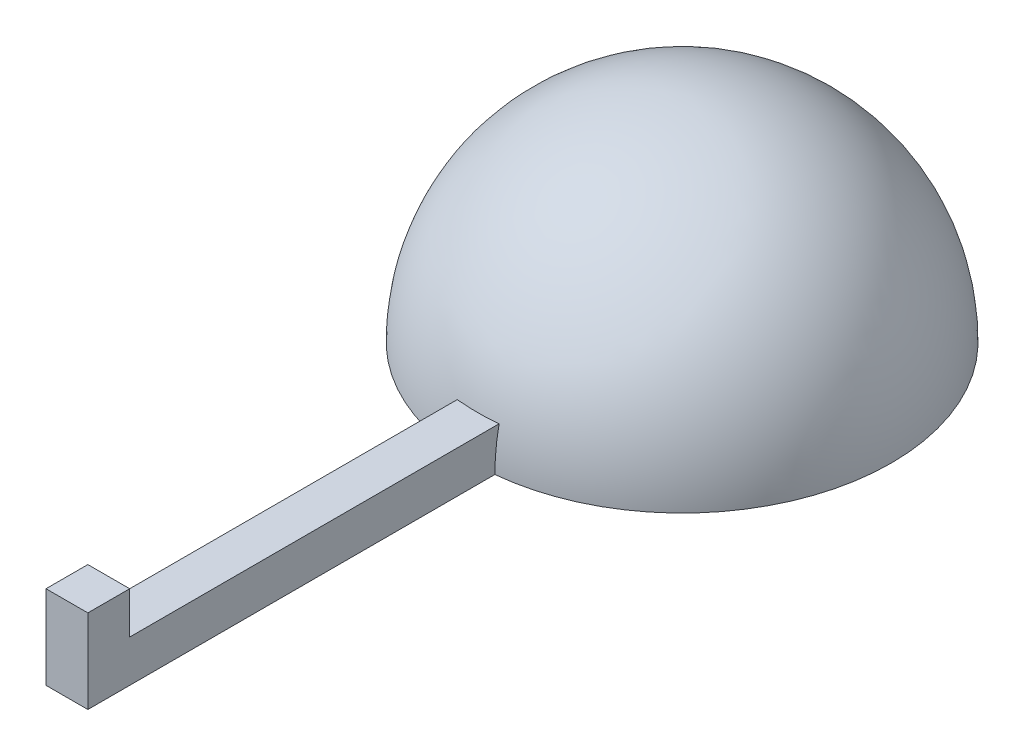
SolidWorks part; units mm, degrees
ref_plane "Front Plane" through (0, 0, 0) normal (0, 0, 1) x (1, 0, 0)
ref_plane "Top Plane" through (0, 0, 0) normal (0, 1, 0) x (1, 0, 0)
ref_plane "Right Plane" through (0, 0, 0) normal (1, 0, 0) x (0, 0, -1)
sketch "Sketch1" plane through (0, 0, 0) normal (0, 1, 0) x (1, 0, 0)
  line L0 (-50, 0) -> (50, 0)
  arc A0 (-50, 0) -> (50, 0) centre (0, 0) cw
  dimension "D1" = 50
revolve "Revolve1" add sketch "Sketch1" angle 180 about L0
shell "Shell3" thickness 3
sketch "Sketch5" plane through (0, 0, 0) normal (1, 0, 0) x (0, 0, -1)
  line L0 (-47, 0) -> (-47, 10)
  line L1 (-47, 10) -> (-137, 10)
  line L2 (-137, 10) -> (-137, 20)
  line L3 (-137, 20) -> (-147, 20)
  line L4 (-147, 20) -> (-147, 0)
  line L5 (-147, 0) -> (-47, 0)
  point P3 (0, 0)
  dimension "D1" = 100
  dimension "D2" = 10
  dimension "D3" = 10
  dimension "D4" = 10
extrude "Boss-Extrude1" add sketch "Sketch5" along normal mid plane 10
